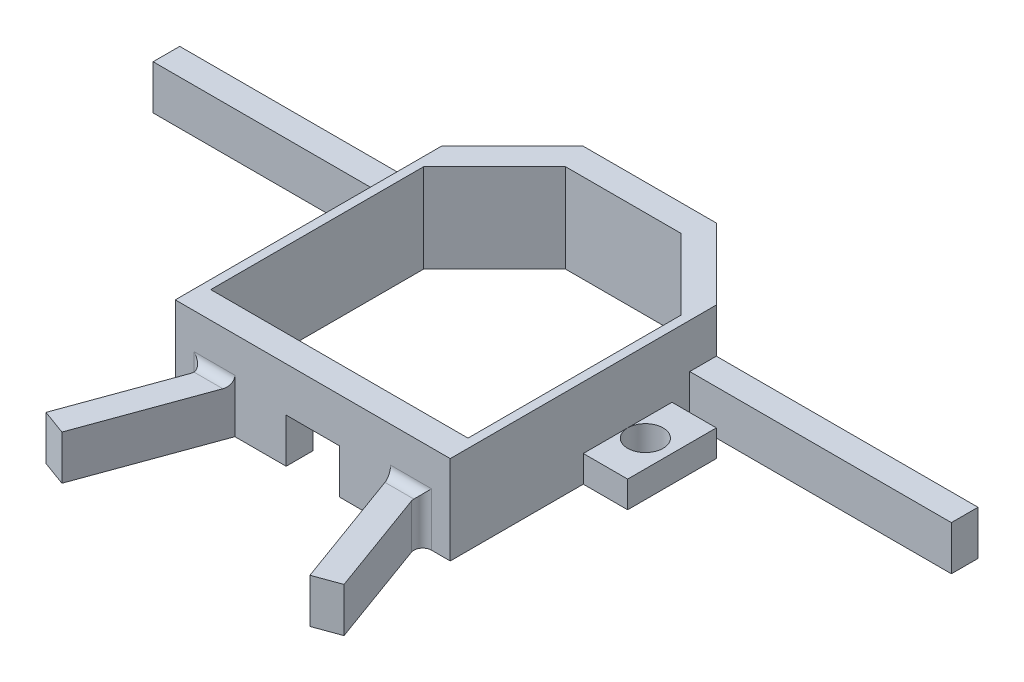
SolidWorks part; units mm, degrees
ref_plane "前视基准面" through (0, 0, 0) normal (0, 0, 1) x (1, 0, 0)
ref_plane "上视基准面" through (0, 0, 0) normal (0, 1, 0) x (1, 0, 0)
ref_plane "右视基准面" through (0, 0, 0) normal (1, 0, 0) x (0, 0, -1)
sketch "Sketch1" plane through (0, 0, 0) normal (0, 1, 0) x (1, 0, 0)
  line L1 (-15.5, -19) -> (15.5, -19)
  line L2 (-15.5, -19) -> (-15.5, 19)
  line L3 (-15.5, 19) -> (15.5, 19)
  line L4 (15.5, -19) -> (15.5, 19)
  line L5 (-15.5, -19) -> (15.5, 19) construction
  line L6 (-15.5, 19) -> (15.5, -19) construction
  line L7 (-14.5, -16) -> (14.5, -16)
  line L8 (-14.5, -16) -> (-14.5, 16)
  line L9 (-14.5, 16) -> (14.5, 16)
  line L10 (14.5, -16) -> (14.5, 16)
  line L11 (-14.5, -16) -> (14.5, 16) construction
  line L12 (-14.5, 16) -> (14.5, -16) construction
  point P0 (0, 0)
  point P6 (0, 0)
  dimension "D1" = 31
  dimension "D2" = 38
  dimension "D3" = 1
  dimension "D4" = 3
extrude "Boss-Extrude1" add sketch "Sketch1" along normal blind 10
sketch "Sketch2" plane through (0, 0, 0) normal (0, -1, 0) x (1, 0, 0)
  line L1 (14.5, 16) -> (14.5, -16) construction
  line L2 (20.5, 4) -> (14.5, 4)
  line L3 (20.5, 4) -> (20.5, -6)
  line L4 (20.5, -6) -> (14.5, -6)
  line L5 (14.5, 4) -> (14.5, -6)
  line L6 (20.5, 4) -> (14.5, -6) construction
  line L7 (20.5, -6) -> (14.5, 4) construction
  line L8 (14.5, -16) -> (-14.5, -16) construction
  circle A0 centre (17.5, -1) radius 2
  point P0 (17.5, -1)
  dimension "D4" = 4
  dimension "D1" = 6
  dimension "D2" = 10
  dimension "D3" = 15
extrude "Boss-Extrude2" add sketch "Sketch2" against normal blind 3
mirror "Mirror1" about plane through (0, 0, 0) normal (1, 0, 0) of "Boss-Extrude2"
sketch "Sketch3" plane through (0, 0, 0) normal (0, -1, 0) x (1, 0, 0)
  line L0 (0, 19) -> (0, 16) construction
  line L1 (-15.5, 19) -> (15.5, 19) construction
  line L2 (-14.5, 16) -> (14.5, 16) construction
  line L4 (-3, 16) -> (3, 16)
  line L5 (-3, 16) -> (-3, 19)
  line L8 (-3, 19) -> (3, 19)
  line L9 (3, 16) -> (3, 19)
  line L10 (-3, 16) -> (3, 19) construction
  line L11 (-3, 19) -> (3, 16) construction
  point P6 (0, 17.5)
  dimension "D1" = 6
extrude "Cut-Extrude1" cut sketch "Sketch3" against normal blind 5
sketch "Sketch4" plane through (0, 0, 0) normal (0, -1, 0) x (1, 0, 0)
  line L0 (0, 0) -> (0, -9.5) construction
  line L1 (0, -9.5) -> (15.3909, 32.7862) construction
  line L2 (0, -9.5) -> (0, 35.5) construction
  line L3 (0, -9.5) -> (45, -9.5) construction
  line L4 (13.9814, 33.2992) -> (16.8004, 32.2731)
  line L5 (16.8004, 32.2731) -> (11.9694, 19)
  line L6 (3, 19) -> (15.5, 19) construction
  line L7 (11.9694, 19) -> (8.7769, 19)
  line L8 (8.7769, 19) -> (13.9814, 33.2992)
  line L9 (45, -8) -> (45, -11)
  line L10 (45, -8) -> (15.5, -8)
  line L13 (15.5, -11) -> (45, -11)
  line L14 (15.5, -11) -> (15.5, -8)
  line L15 (14.5, -16) -> (-14.5, -16) construction
  line L16 (15.5, -6) -> (15.5, -19) construction
  circle A0 centre (0, -9.5) radius 45 construction
  dimension "D2" = 90
  dimension "D1" = 6.5
  dimension "D3" = 20
  dimension "D5" = 3
  dimension "D6" = 3
extrude "Boss-Extrude3" add sketch "Sketch4" against normal blind 5
fillet "Fillet1" radius 1 2 edges at (10.3732, 5, 19)
chamfer "Chamfer1" distance 8 angle 45 4 edges at (15.5, 5, -19) (-15.5, 5, -19) (14.5, 5, -16) (-14.5, 5, -16)
mirror "Mirror2" about plane through (0, 0, 0) normal (1, 0, 0) of "Fillet1", "Boss-Extrude3"
